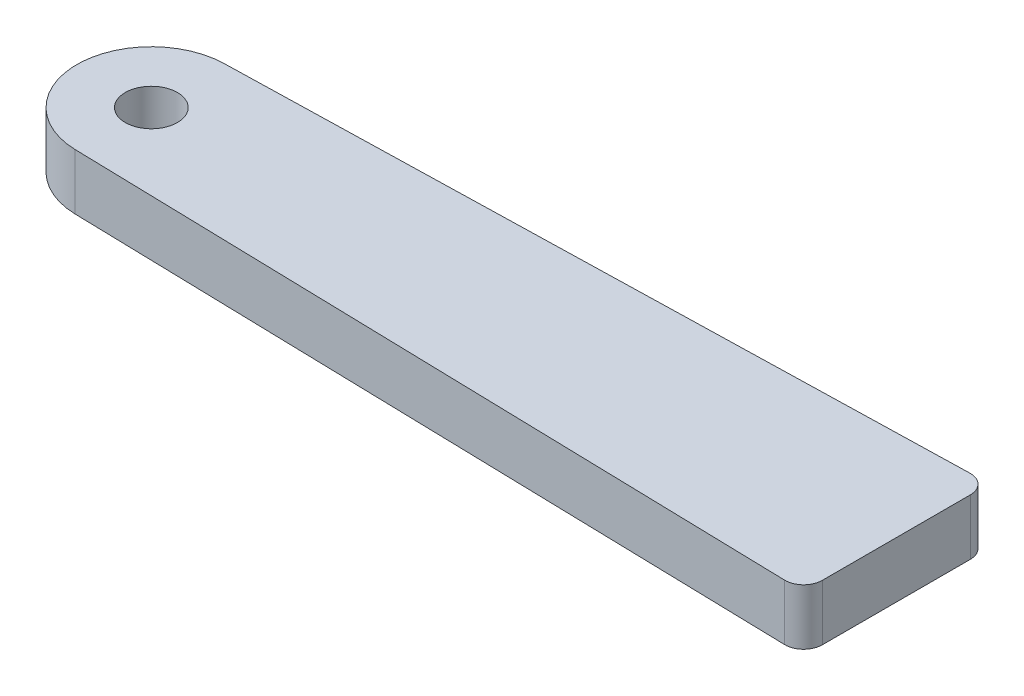
SolidWorks part; units mm, degrees
ref_plane "Front Plane" through (0, 0, 0) normal (0, 0, 1) x (1, 0, 0)
ref_plane "Top Plane" through (0, 0, 0) normal (0, 1, 0) x (1, 0, 0)
ref_plane "Right Plane" through (0, 0, 0) normal (1, 0, 0) x (0, 0, -1)
sketch "Sketch1" plane through (0, 0, 0) normal (0, 1, 0) x (1, 0, 0)
  line L0 (-1.025, -0.0256) -> (-40.0999, -1.0012)
  line L2 (0, -1.0253) -> (0, -8.9747)
  line L5 (-1.0249, -9.9744) -> (-40.0998, -8.9994)
  circle A1 centre (-40, -5.0003) radius 1.4
  arc A3 (-40.0999, -1.0012) -> (-40.0998, -8.9994) centre (-40, -5.0003) ccw
  arc A4 (-1.0249, -9.9744) -> (0, -8.9747) centre (-1, -8.9747) ccw
  arc A5 (0, -1.0253) -> (-1.025, -0.0256) centre (-1, -1.0253) ccw
  point P11 (0, 0)
  dimension "D1" = 1
extrude "Boss-Extrude1" add sketch "Sketch1" along normal blind 3 contours L2 A5 L0 A3 L5 A4 A1
